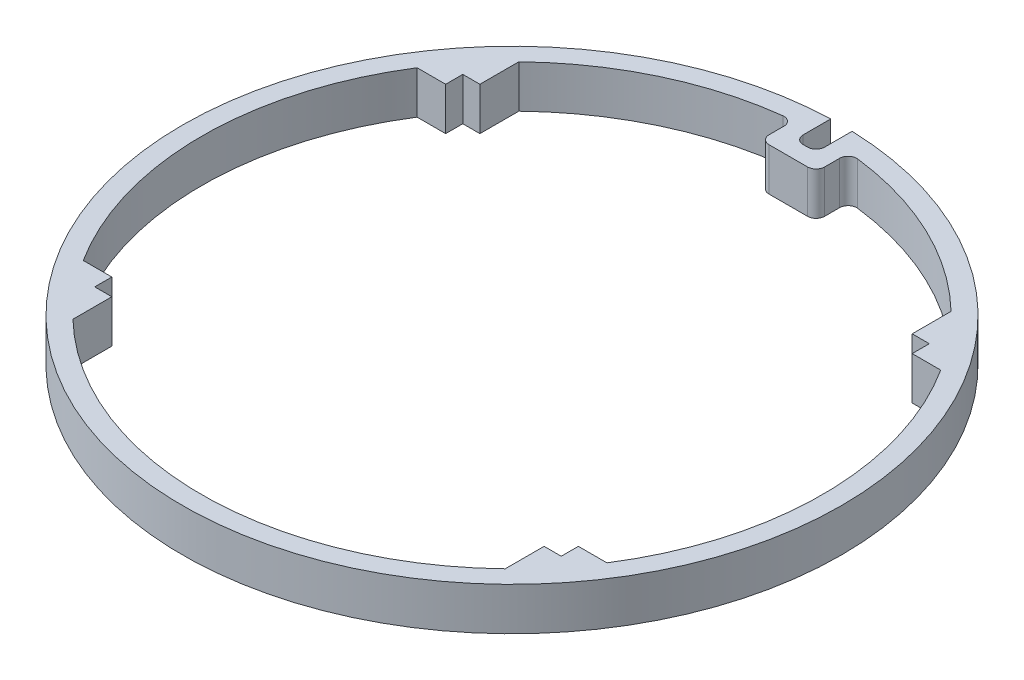
SolidWorks part; units mm, degrees
ref_plane "Front Plane" through (0, 0, 0) normal (0, 0, 1) x (1, 0, 0)
ref_plane "Top Plane" through (0, 0, 0) normal (0, 1, 0) x (1, 0, 0)
ref_plane "Right Plane" through (0, 0, 0) normal (1, 0, 0) x (0, 0, -1)
sketch "Sketch1" plane through (0, 0, 0) normal (0, 1, 0) x (1, 0, 0)
  line L4 (-0.5, 68.5483) -> (0.5, 68.5483)
  line L13 (-4.4989, 64.5455) -> (4.5046, 64.5455)
  line L25 (50.5, 52.0889) -> (50.5, 43)
  line L27 (54.5, 39) -> (61.176, 39)
  line L29 (50.5, -52.0889) -> (50.5, -43)
  line L31 (54.5, -39) -> (61.176, -39)
  line L33 (-54.5, -39) -> (-61.176, -39)
  line L35 (-50.5, -43) -> (-50.5, -52.0889)
  line L36 (-6.4989, 70.0362) -> (-6.4989, 66.5455)
  line L37 (-2.5, 76.5092) -> (-2.5, 70.5483)
  line L38 (6.5046, 66.5455) -> (6.5046, 70.0355)
  line L39 (-54.5, 39) -> (-54.5, 43)
  line L42 (-54.5, 43) -> (-50.5, 43)
  line L43 (-50.5, 52.0889) -> (-50.5, 43)
  line L44 (-54.5, 39) -> (-61.176, 39)
  line L45 (-54.5, -39) -> (-54.5, -43)
  line L46 (-54.5, -43) -> (-50.5, -43)
  line L47 (54.5, -39) -> (54.5, -43)
  line L48 (54.5, -43) -> (50.5, -43)
  line L49 (50.5, 43) -> (54.5, 43)
  line L50 (54.5, 43) -> (54.5, 39)
  line L51 (2.5, 76.5092) -> (2.5, 70.5483)
  arc A0 (-2.5, 76.5092) -> (2.5, 76.5092) centre (0, 0) ccw
  arc A1 (-8.7398, 72.0216) -> (-50.5, 52.0889) centre (0, 0) ccw
  arc A2 (6.5046, 70.0355) -> (8.7457, 72.0209) centre (8.5046, 70.0355) cw
  arc A3 (-6.4989, 70.0362) -> (-8.7398, 72.0216) centre (-8.4989, 70.0362) ccw
  arc A4 (-2.5, 70.5483) -> (-0.5, 68.5483) centre (-0.5, 70.5483) ccw
  arc A5 (0.5, 68.5483) -> (2.5, 70.5483) centre (0.5, 70.5483) ccw
  arc A6 (4.5046, 64.5455) -> (6.5046, 66.5455) centre (4.5046, 66.5455) ccw
  arc A7 (-6.4989, 66.5455) -> (-4.4989, 64.5455) centre (-4.4989, 66.5455) ccw
  arc A9 (-50.5, -52.0889) -> (50.5, -52.0889) centre (0, 0) ccw
  arc A10 (61.176, -39) -> (61.176, 39) centre (0, 0) ccw
  arc A11 (50.5, 52.0889) -> (8.7457, 72.0209) centre (0, 0) ccw
  arc A12 (-61.176, 39) -> (-61.176, -39) centre (0.3145, 0) ccw
  dimension "D1" = 2
  dimension "D5" = 76.55
extrude "Boss-Extrude1" add sketch "Sketch1" along normal blind 10
sketch "Sketch2" plane through (0, 10, 0) normal (0, 1, 0) x (1, 0, 0)
  line L0 (-2.5, 76.5092) -> (-2.5, 76.9594)
  line L1 (2.5, 76.5092) -> (2.5, 76.9594)
  line L2 (-2.5, 70.5483) -> (-2.5, 76.5092)
  line L3 (2.5, 76.5092) -> (2.5, 70.5483)
  line L4 (-0.5, 68.5483) -> (0.5, 68.5483)
  line L5 (-3.6307, 67.2129) -> (-5.9146, 74.5612)
  line L6 (-5.9146, 74.5612) -> (-38.6053, 64.4005)
  line L7 (-38.6053, 64.4005) -> (-65.1968, 38.1676)
  line L8 (-65.1968, 38.1676) -> (-75.3554, 0.677)
  line L9 (-75.3554, 0.677) -> (-66.862, -35.9876)
  line L10 (-66.862, -35.9876) -> (-44.3224, -61.0243)
  line L11 (-44.3224, -61.0243) -> (-15.4441, -74.0411)
  line L12 (-15.4441, -74.0411) -> (24.7713, -71.6634)
  line L13 (24.7713, -71.6634) -> (56.953, -49.6932)
  line L14 (56.953, -49.6932) -> (72.7871, -20.4995)
  line L15 (72.7871, -20.4995) -> (73.8913, 14.6557)
  line L16 (73.8913, 14.6557) -> (57.8178, 48.7048)
  line L17 (57.8178, 48.7048) -> (30.4054, 68.5483)
  line L18 (30.4054, 68.5483) -> (5.8037, 74.1743)
  line L19 (5.8037, 74.1743) -> (4.2118, 67.2129)
  line L20 (4.2118, 67.2129) -> (-3.6307, 67.2129)
  arc A0 (-2.5, 76.9594) -> (2.5, 76.9594) centre (0, 0) ccw
  arc A1 (2.5, 70.5483) -> (0.5, 68.5483) centre (0.5, 70.5483) cw
  arc A2 (-2.5, 70.5483) -> (-0.5, 68.5483) centre (-0.5, 70.5483) ccw
extrude "Boss-Extrude2" add sketch "Sketch2" against normal blind 10 contours A0 L1 L3 A1 L4 A2 L2 L0 | L20 L5 L6 L7 L8 L9 L10 L11 L12 L13 L14 L15 L16 L17 L18 L19
